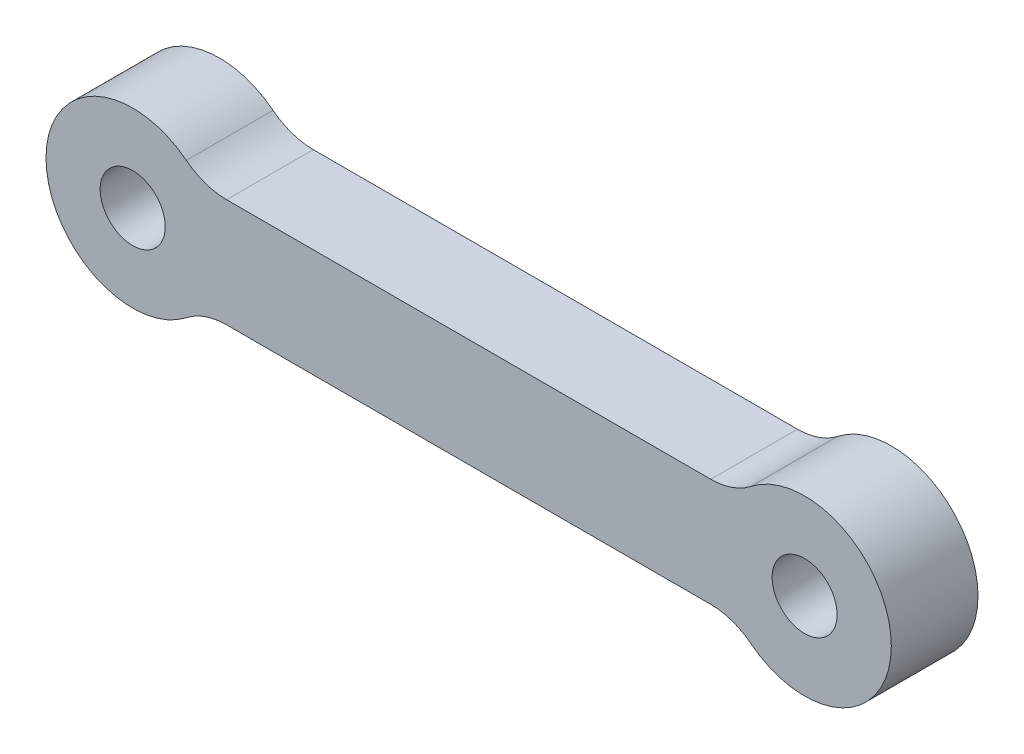
SolidWorks part; units mm, degrees
ref_plane "Front Plane" through (0, 0, 0) normal (0, 0, 1) x (1, 0, 0)
ref_plane "Top Plane" through (0, 0, 0) normal (0, 1, 0) x (1, 0, 0)
ref_plane "Right Plane" through (0, 0, 0) normal (1, 0, 0) x (0, 0, -1)
sketch "Sketch1" plane through (0, 0, 0) normal (0, 0, 1) x (1, 0, 0)
  line L0 (-15.5, 0) -> (15.5, 0) construction
  line L1 (0, 0) -> (0, 2.3485) construction
  line L3 (-11.1699, 2.5) -> (11.1699, 2.5)
  line L5 (-11.1699, -2.5) -> (11.1699, -2.5)
  line L7 (-12.3775, 2.5) -> (12.3775, -2.5) construction
  line L8 (-12.3775, -2.5) -> (12.3775, 2.5) construction
  circle A0 centre (-15.5, 0) radius 1.5
  arc A1 (-13.0256, 3.1429) -> (-13.0256, -3.1429) centre (-15.5, 0) ccw
  arc A2 (13.0256, 3.1429) -> (13.0256, -3.1429) centre (15.5, 0) cw
  circle A3 centre (15.5, 0) radius 1.5
  arc A4 (11.1699, 2.5) -> (13.0256, 3.1429) centre (11.1699, 5.5) ccw
  arc A5 (11.1699, -2.5) -> (13.0256, -3.1429) centre (11.1699, -5.5) cw
  arc A6 (-13.0256, -3.1429) -> (-11.1699, -2.5) centre (-11.1699, -5.5) cw
  arc A7 (-11.1699, 2.5) -> (-13.0256, 3.1429) centre (-11.1699, 5.5) cw
  point P4 (0, 0)
  point P15 (0, 0)
  point P16 (0, 0)
  point P17 (0, 0)
  point P18 (0, 0)
  point P19 (-12.3686, 2.4888)
  point P20 (0, 0)
  dimension "D2" = 8
  dimension "D3" = 3
  dimension "D5" = 3
  dimension "D1" = 31
  dimension "D4" = 5
extrude "Boss-Extrude1" add sketch "Sketch1" along normal blind 4
